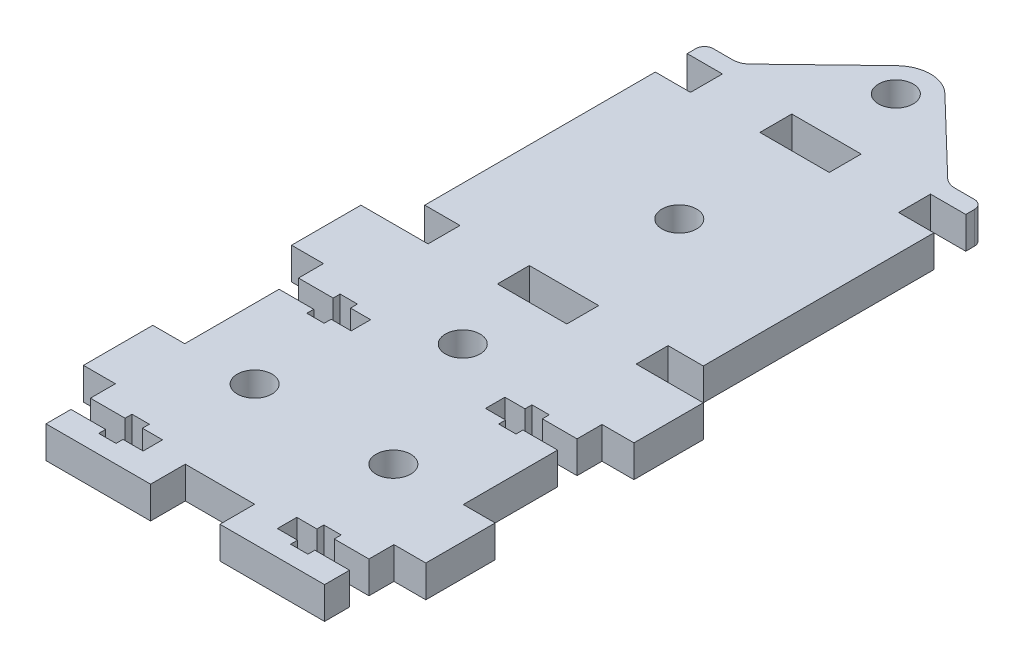
SolidWorks part; units mm, degrees
ref_plane "Front Plane" through (0, 0, 0) normal (0, 0, 1) x (1, 0, 0)
ref_plane "Top Plane" through (0, 0, 0) normal (0, 1, 0) x (1, 0, 0)
ref_plane "Right Plane" through (0, 0, 0) normal (1, 0, 0) x (0, 0, -1)
sketch "Sketch1" plane through (0, 0, 0) normal (0, 1, 0) x (1, 0, 0)
  line L0 (19.05, 24.0268) -> (6.35, 24.0268) construction
  line L1 (25.5, -21.1058) -> (19.05, -21.1058)
  line L2 (25.5, -21.1058) -> (25.5, 21.1058)
  line L3 (25.5, 21.1058) -> (19.05, 21.1058)
  line L4 (-25.5, -21.1058) -> (-25.5, 21.1058)
  line L5 (0, 21.1058) -> (0, -21.1058) construction
  line L6 (25.5, 0) -> (-25.5, 0) construction
  line L7 (-19.05, 26.9478) -> (-25.5, 26.9478)
  line L8 (-19.05, 26.9478) -> (-19.05, 21.1058)
  line L9 (25.5, 21.1058) -> (25.5, 26.9478) construction
  line L10 (-6.35, 26.9478) -> (-6.35, 21.1058)
  line L11 (-12.7, 21.1058) -> (-12.7, 26.9478) construction
  line L12 (-19.05, 24.0268) -> (-6.35, 24.0268) construction
  line L13 (12.7, 21.1058) -> (12.7, 26.9478) construction
  line L14 (6.35, 26.9478) -> (6.35, 21.1058)
  line L15 (-19.05, 21.1058) -> (-25.5, 21.1058)
  line L16 (19.05, 26.9478) -> (19.05, 21.1058)
  line L17 (0, -21.1058) -> (0, -65.0478) construction
  line L18 (12.7, -21.1058) -> (12.7, -26.9478) construction
  line L19 (-19.05, -24.0268) -> (-6.35, -24.0268) construction
  line L20 (-12.7, -21.1058) -> (-12.7, -26.9478) construction
  line L21 (19.05, -24.0268) -> (6.35, -24.0268) construction
  line L22 (31.342, -33.2978) -> (25.5, -33.2978) construction
  line L23 (19.05, -26.9478) -> (19.05, -21.1058)
  line L24 (6.35, 21.1058) -> (-6.35, 21.1058)
  line L25 (6.35, -26.9478) -> (6.35, -21.1058)
  line L26 (-6.35, -26.9478) -> (-6.35, -21.1058)
  line L27 (6.35, -21.1058) -> (-6.35, -21.1058)
  line L28 (-19.05, -26.9478) -> (-19.05, -21.1058)
  line L29 (6.35, -26.9478) -> (-6.35, -26.9478)
  line L30 (-19.05, -21.1058) -> (-25.5, -21.1058)
  line L31 (25.5, 30.1228) -> (-25.5, 30.1228)
  line L32 (25.5, 30.1228) -> (25.5, 26.9478)
  line L33 (25.5, 26.9478) -> (19.05, 26.9478)
  line L34 (-25.5, 30.1228) -> (-25.5, 26.9478)
  line L35 (0, 26.9478) -> (0, 30.1228) construction
  line L36 (25.5, 28.5353) -> (-25.5, 28.5353) construction
  line L37 (6.35, 26.9478) -> (-6.35, 26.9478)
  line L38 (-19.05, -26.9478) -> (-25.5, -26.9478)
  line L39 (-25.5, -39.6478) -> (-25.5, -65.0478)
  line L40 (-31.342, -77.7478) -> (-25.5, -77.7478)
  line L41 (25.5, -26.9478) -> (19.05, -26.9478)
  line L42 (-31.342, -77.7478) -> (-31.342, -65.0478)
  line L43 (0, -26.9478) -> (0, -103.1478) construction
  line L44 (25.5, -65.0478) -> (-25.5, -65.0478) construction
  line L45 (-31.342, -39.6478) -> (-25.5, -39.6478)
  line L46 (-31.342, -39.6478) -> (-31.342, -26.9478)
  line L47 (-31.342, -26.9478) -> (-25.5, -26.9478)
  line L48 (28.421, -26.9478) -> (28.421, -39.6478) construction
  line L49 (-28.421, -26.9478) -> (-28.421, -39.6478) construction
  line L50 (-31.342, -33.2978) -> (-25.5, -33.2978) construction
  line L51 (31.342, -26.9478) -> (25.5, -26.9478)
  line L52 (31.342, -39.6478) -> (31.342, -26.9478)
  line L53 (31.342, -39.6478) -> (25.5, -39.6478)
  line L54 (-31.342, -65.0478) -> (-25.5, -65.0478)
  line L55 (-25.5, -77.7478) -> (-25.5, -90.4478)
  line L56 (25.5, -39.6478) -> (25.5, -65.0478)
  line L57 (25.5, -77.7478) -> (25.5, -90.4478)
  line L58 (31.342, -65.0478) -> (25.5, -65.0478)
  line L59 (31.342, -77.7478) -> (31.342, -65.0478)
  line L60 (31.342, -77.7478) -> (25.5, -77.7478)
  line L61 (-31.342, -71.3978) -> (31.342, -71.3978) construction
  line L62 (6.35, -90.4478) -> (26.8151, -90.4478)
  line L63 (-25.5, -90.4478) -> (-6.35, -90.4478)
  line L64 (6.35, -84.0978) -> (-6.35, -84.0978)
  line L65 (6.35, -84.0978) -> (6.35, -90.4478)
  line L67 (-6.35, -84.0978) -> (-6.35, -90.4478)
  line L68 (6.35, -84.0978) -> (-6.35, -90.4478) construction
  line L69 (6.35, -90.4478) -> (-6.35, -84.0978) construction
  circle A0 centre (-12.7, -71.3978) radius 3.175 construction
  circle A1 centre (12.7, -71.3978) radius 3.175 construction
  point P0 (0, 0)
  point P4 (-12.7, 24.0268)
  point P16 (12.7, 24.0268)
  point P39 (12.7, -24.0268)
  point P40 (-12.7, -24.0268)
  point P41 (0, 28.5353)
  point P49 (-28.421, -33.2978)
  point P59 (28.421, -33.2978)
  point P74 (0, -87.2728)
  dimension "D12" = 12.7
  dimension "D1" = 51
  dimension "D2" = 42.2116
  dimension "D3" = 5.842
  dimension "D4" = 12.7
  dimension "D5" = 12.7
  dimension "D6" = 3.175
  dimension "D7" = 51
  dimension "D8" = 63.5
  dimension "D9" = 12.7
  dimension "D10" = 5.842
  dimension "D13" = 6.35
  dimension "D11" = 2
extrude "Boss-Extrude1" add sketch "Sketch1" along normal blind 5.842
fillet "Fillet1" radius 1.5875 2 edges at (25.5, 2.921, -30.1228) (-25.5, 2.921, -30.1228)
sketch "Sketch2" plane through (0, 5.842, 0) normal (0, 1, 0) x (1, 0, 0)
  line L0 (-25.5, -45.9978) -> (25.5, -45.9978) construction
  line L1 (-25.5, -39.6478) -> (-25.5, -65.0478) construction
  line L2 (25.5, -39.6478) -> (25.5, -65.0478) construction
  line L3 (-31.342, -39.6478) -> (-25.5, -39.6478) construction
  line L4 (-19.15, -44.2198) -> (-19.15, -42.9498)
  line L5 (-19.15, -47.7758) -> (-25.5, -47.7758)
  line L6 (-15.975, -44.2198) -> (-15.975, -42.9498)
  line L7 (-19.15, -44.2198) -> (-25.5, -44.2198)
  line L8 (-25.5, -47.7758) -> (-25.5, -44.2198)
  line L9 (-19.15, -47.7758) -> (-25.5, -44.2198) construction
  line L10 (-19.15, -44.2198) -> (-25.5, -47.7758) construction
  line L11 (-15.975, -49.0458) -> (-19.15, -49.0458)
  line L12 (-15.975, -49.0458) -> (-15.975, -47.7758)
  line L13 (-15.975, -42.9498) -> (-19.15, -42.9498)
  line L14 (-19.15, -49.0458) -> (-19.15, -47.7758)
  line L15 (-15.975, -49.0458) -> (-19.15, -42.9498) construction
  line L16 (-15.975, -42.9498) -> (-19.15, -49.0458) construction
  line L17 (-12.292, -47.7758) -> (-15.975, -47.7758)
  line L18 (-12.292, -47.7758) -> (-12.292, -44.2198)
  line L19 (-12.292, -44.2198) -> (-15.975, -44.2198)
  line L20 (0, -26.9478) -> (0, -84.0978) construction
  line L21 (-12.292, -47.7758) -> (-15.975, -44.2198) construction
  line L22 (-12.292, -44.2198) -> (-15.975, -47.7758) construction
  line L23 (6.35, -26.9478) -> (-6.35, -26.9478) construction
  line L24 (6.35, -84.0978) -> (-6.35, -84.0978) construction
  line L25 (12.292, -44.2198) -> (15.975, -47.7758) construction
  line L26 (12.292, -47.7758) -> (15.975, -44.2198) construction
  line L27 (15.975, -42.9498) -> (19.15, -49.0458) construction
  line L28 (15.975, -49.0458) -> (19.15, -42.9498) construction
  line L29 (19.15, -44.2198) -> (25.5, -47.7758) construction
  line L30 (19.15, -47.7758) -> (25.5, -44.2198) construction
  line L31 (12.292, -44.2198) -> (15.975, -44.2198)
  line L32 (12.292, -47.7758) -> (12.292, -44.2198)
  line L33 (12.292, -47.7758) -> (15.975, -47.7758)
  line L34 (19.15, -49.0458) -> (19.15, -47.7758)
  line L35 (15.975, -42.9498) -> (19.15, -42.9498)
  line L36 (15.975, -49.0458) -> (15.975, -47.7758)
  line L37 (15.975, -49.0458) -> (19.15, -49.0458)
  line L38 (25.5, -47.7758) -> (25.5, -44.2198)
  line L39 (19.15, -44.2198) -> (25.5, -44.2198)
  line L40 (15.975, -44.2198) -> (15.975, -42.9498)
  line L41 (19.15, -47.7758) -> (25.5, -47.7758)
  line L42 (19.15, -44.2198) -> (19.15, -42.9498)
  line L43 (-25.5, -65.0478) -> (25.5, -65.0478) construction
  line L46 (19.15, -82.3198) -> (25.5, -85.8758) construction
  line L47 (19.15, -85.8758) -> (25.5, -82.3198) construction
  line L48 (15.975, -81.0498) -> (19.15, -87.1458) construction
  line L49 (15.975, -87.1458) -> (19.15, -81.0498) construction
  line L50 (12.292, -82.3198) -> (15.975, -85.8758) construction
  line L51 (12.292, -85.8758) -> (15.975, -82.3198) construction
  line L52 (-12.292, -85.8758) -> (-15.975, -82.3198) construction
  line L53 (-12.292, -82.3198) -> (-15.975, -85.8758) construction
  line L54 (-15.975, -87.1458) -> (-19.15, -81.0498) construction
  line L55 (-15.975, -81.0498) -> (-19.15, -87.1458) construction
  line L56 (-19.15, -85.8758) -> (-25.5, -82.3198) construction
  line L57 (-19.15, -82.3198) -> (-25.5, -85.8758) construction
  line L58 (-25.5, -84.0978) -> (25.5, -84.0978) construction
  line L59 (19.15, -85.8758) -> (19.15, -87.1458)
  line L60 (19.15, -82.3198) -> (25.5, -82.3198)
  line L61 (15.975, -85.8758) -> (15.975, -87.1458)
  line L62 (19.15, -85.8758) -> (25.5, -85.8758)
  line L63 (25.5, -82.3198) -> (25.5, -85.8758)
  line L64 (15.975, -81.0498) -> (19.15, -81.0498)
  line L65 (15.975, -81.0498) -> (15.975, -82.3198)
  line L66 (15.975, -87.1458) -> (19.15, -87.1458)
  line L67 (19.15, -81.0498) -> (19.15, -82.3198)
  line L68 (12.292, -82.3198) -> (15.975, -82.3198)
  line L69 (12.292, -82.3198) -> (12.292, -85.8758)
  line L70 (12.292, -85.8758) -> (15.975, -85.8758)
  line L71 (-12.292, -85.8758) -> (-15.975, -85.8758)
  line L72 (-12.292, -82.3198) -> (-12.292, -85.8758)
  line L73 (-12.292, -82.3198) -> (-15.975, -82.3198)
  line L74 (-19.15, -81.0498) -> (-19.15, -82.3198)
  line L75 (-15.975, -87.1458) -> (-19.15, -87.1458)
  line L76 (-15.975, -81.0498) -> (-15.975, -82.3198)
  line L77 (-15.975, -81.0498) -> (-19.15, -81.0498)
  line L78 (-25.5, -82.3198) -> (-25.5, -85.8758)
  line L79 (-19.15, -85.8758) -> (-25.5, -85.8758)
  line L80 (-15.975, -85.8758) -> (-15.975, -87.1458)
  line L81 (-19.15, -82.3198) -> (-25.5, -82.3198)
  line L82 (-19.15, -85.8758) -> (-19.15, -87.1458)
  point P8 (-22.325, -45.9978)
  point P13 (-17.5625, -45.9978)
  point P18 (-14.1335, -45.9978)
  point P41 (14.1335, -45.9978)
  point P42 (17.5625, -45.9978)
  point P43 (22.325, -45.9978)
  point P72 (22.325, -84.0978)
  point P73 (17.5625, -84.0978)
  point P74 (14.1335, -84.0978)
  point P75 (-14.1335, -84.0978)
  point P76 (-17.5625, -84.0978)
  point P77 (-22.325, -84.0978)
  dimension "D1" = 6.35
  dimension "D2" = 3.556
  dimension "D3" = 6.35
  dimension "D4" = 3.175
  dimension "D5" = 6.096
  dimension "D6" = 3.556
  dimension "D7" = 3.683
  dimension "D8" = 19.05
extrude "Cut-Extrude1" cut sketch "Sketch2" against normal through all
sketch "Sketch3" plane through (0, 5.842, 0) normal (0, 1, 0) x (1, 0, 0)
  line L0 (0, 30.1228) -> (0, -84.0978) construction
  line L1 (23.9125, 30.1228) -> (-23.9125, 30.1228) construction
  line L2 (6.35, -84.0978) -> (-6.35, -84.0978) construction
  line L3 (-25.5, -65.0478) -> (25.5, -65.0478) construction
  circle A0 centre (0, 0) radius 3.175
  circle A1 centre (-12.7, -65.0478) radius 3.175
  circle A2 centre (12.7, -65.0478) radius 3.175
  circle A3 centre (0, -39.6478) radius 3.175
  dimension "D1" = 6.35
  dimension "D2" = 6.35
  dimension "D4" = 6.35
  dimension "D3" = 12.7
  dimension "D5" = 25.4
extrude "Cut-Extrude2" cut sketch "Sketch3" against normal through all
sketch "Sketch4" plane through (0, 5.842, 0) normal (0, 1, 0) x (1, 0, 0)
  line L0 (0, 21.1058) -> (0, 39.6478) construction
  line L1 (6.35, 21.1058) -> (-6.35, 21.1058) construction
  line L2 (23.9125, 30.1228) -> (-23.9125, 30.1228) construction
  line L3 (-19.05, 30.1228) -> (-4.404, 44.2224)
  line L4 (19.05, 30.1228) -> (4.404, 44.2224)
  line L5 (-19.05, 30.1228) -> (19.05, 30.1228)
  circle A0 centre (0, 39.6478) radius 3.175
  arc A1 (4.404, 44.2224) -> (-4.404, 44.2224) centre (0, 39.6478) ccw
  circle A3 centre (0, 39.6478) radius 6.35 construction
  point P14 (6.35, 39.6478)
  dimension "D2" = 6.35
  dimension "D1" = 9.525
  dimension "D3" = 3.175
extrude "Boss-Extrude2" add sketch "Sketch4" against normal up to surface (5.842 mm away) up to face at (0, 0, 42.8228)
fillet "Fillet2" radius 3.175 2 edges at (19.05, 2.921, -30.1228) (-19.05, 2.921, -30.1228)
